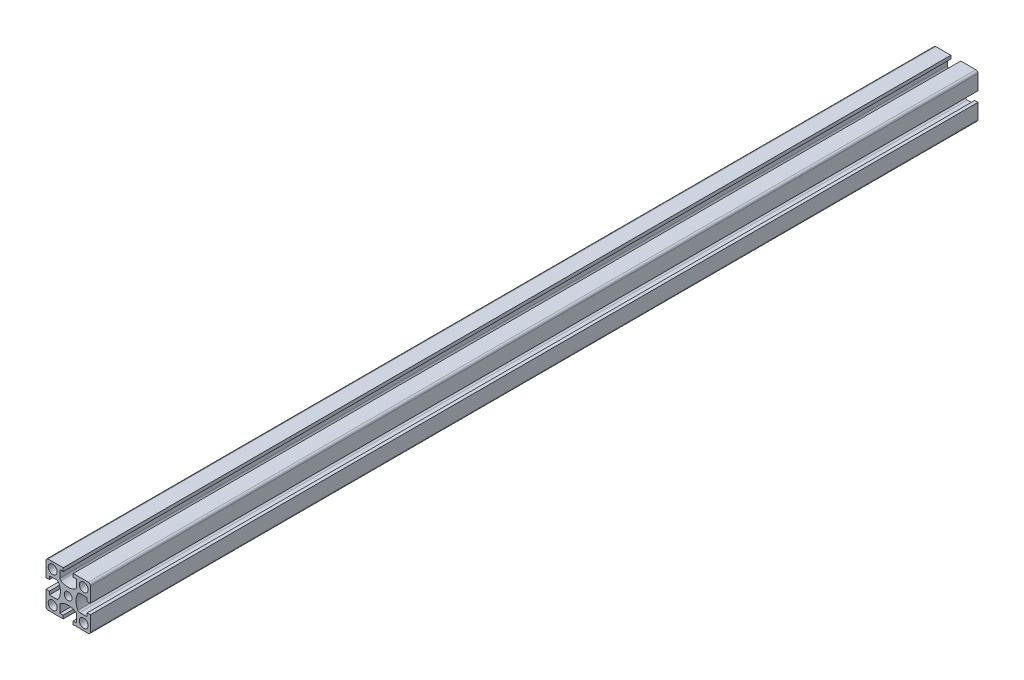
SolidWorks part; units mm, degrees
ref_plane "Front Plane" through (0, 0, 0) normal (0, 0, 1) x (1, 0, 0)
ref_plane "Top Plane" through (0, 0, 0) normal (0, 1, 0) x (1, 0, 0)
ref_plane "Right Plane" through (0, 0, 0) normal (1, 0, 0) x (0, 0, -1)
sketch "Sketch1" plane through (0, 0, 0) normal (0, 0, 1) x (1, 0, 0)
  line L64 (-12.5, 11.25) -> (-12.5, 2.8125)
  line L65 (-12.5, 2.8125) -> (-10.625, 2.8125)
  line L66 (-10.625, 2.8125) -> (-10.625, 4.6875)
  line L67 (-10.625, 4.6875) -> (-6.5461, 4.6875)
  line L68 (-6.5461, -4.6875) -> (-10.625, -4.6875)
  line L69 (-10.625, -4.6875) -> (-10.625, -2.8125)
  line L70 (-10.625, -2.8125) -> (-12.5, -2.8125)
  line L71 (-12.5, -2.8125) -> (-12.5, -11.25)
  line L72 (-11.25, -12.5) -> (-2.8125, -12.5)
  line L73 (-2.8125, -12.5) -> (-2.8125, -10.625)
  line L74 (-2.8125, -10.625) -> (-4.6875, -10.625)
  line L75 (-4.6875, -10.625) -> (-4.6875, -6.5461)
  line L76 (4.6875, -6.5461) -> (4.6875, -10.625)
  line L77 (4.6875, -10.625) -> (2.8125, -10.625)
  line L78 (2.8125, -10.625) -> (2.8125, -12.5)
  line L79 (2.8125, -12.5) -> (11.25, -12.5)
  line L80 (12.5, -11.25) -> (12.5, -2.8125)
  line L81 (12.5, -2.8125) -> (10.625, -2.8125)
  line L82 (10.625, -2.8125) -> (10.625, -4.6875)
  line L83 (10.625, -4.6875) -> (6.5461, -4.6875)
  line L84 (6.5461, 4.6875) -> (10.625, 4.6875)
  line L85 (10.625, 4.6875) -> (10.625, 2.8125)
  line L86 (10.625, 2.8125) -> (12.5, 2.8125)
  line L87 (12.5, 2.8125) -> (12.5, 11.25)
  line L88 (11.25, 12.5) -> (2.8125, 12.5)
  line L89 (2.8125, 12.5) -> (2.8125, 10.625)
  line L90 (2.8125, 10.625) -> (4.6875, 10.625)
  line L91 (4.6875, 10.625) -> (4.6875, 6.5461)
  line L92 (-4.6875, 6.5461) -> (-4.6875, 10.625)
  line L93 (-4.6875, 10.625) -> (-2.8125, 10.625)
  line L94 (-2.8125, 10.625) -> (-2.8125, 12.5)
  line L95 (-2.8125, 12.5) -> (-11.25, 12.5)
  circle A5 centre (-8.75, -8.75) radius 2.5
  circle A6 centre (8.75, -8.75) radius 2.5
  circle A7 centre (8.75, 8.75) radius 2.5
  circle A8 centre (0, 0) radius 2.1875
  circle A9 centre (-8.75, 8.75) radius 2.5
  arc A32 (-11.25, 12.5) -> (-12.5, 11.25) centre (-11.25, 11.25) ccw
  arc A33 (-5.4635, 4.0625) -> (-6.5461, 4.6875) centre (-6.5461, 3.4375) ccw
  arc A34 (-5.4635, -4.0625) -> (-5.4635, 4.0625) centre (-12.5, 0) ccw
  arc A35 (-6.5461, -4.6875) -> (-5.4635, -4.0625) centre (-6.5461, -3.4375) ccw
  arc A36 (-12.5, -11.25) -> (-11.25, -12.5) centre (-11.25, -11.25) ccw
  arc A37 (-4.0625, -5.4635) -> (-4.6875, -6.5461) centre (-3.4375, -6.5461) ccw
  arc A38 (4.0625, -5.4635) -> (-4.0625, -5.4635) centre (0, -12.5) ccw
  arc A39 (4.6875, -6.5461) -> (4.0625, -5.4635) centre (3.4375, -6.5461) ccw
  arc A40 (11.25, -12.5) -> (12.5, -11.25) centre (11.25, -11.25) ccw
  arc A41 (5.4635, -4.0625) -> (6.5461, -4.6875) centre (6.5461, -3.4375) ccw
  arc A42 (5.4635, 4.0625) -> (5.4635, -4.0625) centre (12.5, 0) ccw
  arc A43 (6.5461, 4.6875) -> (5.4635, 4.0625) centre (6.5461, 3.4375) ccw
  arc A44 (12.5, 11.25) -> (11.25, 12.5) centre (11.25, 11.25) ccw
  arc A45 (4.0625, 5.4635) -> (4.6875, 6.5461) centre (3.4375, 6.5461) ccw
  arc A46 (-4.0625, 5.4635) -> (4.0625, 5.4635) centre (0, 12.5) ccw
  arc A47 (-4.6875, 6.5461) -> (-4.0625, 5.4635) centre (-3.4375, 6.5461) ccw
extrude "Boss-Extrude1" add sketch "Sketch1" along normal blind 500
